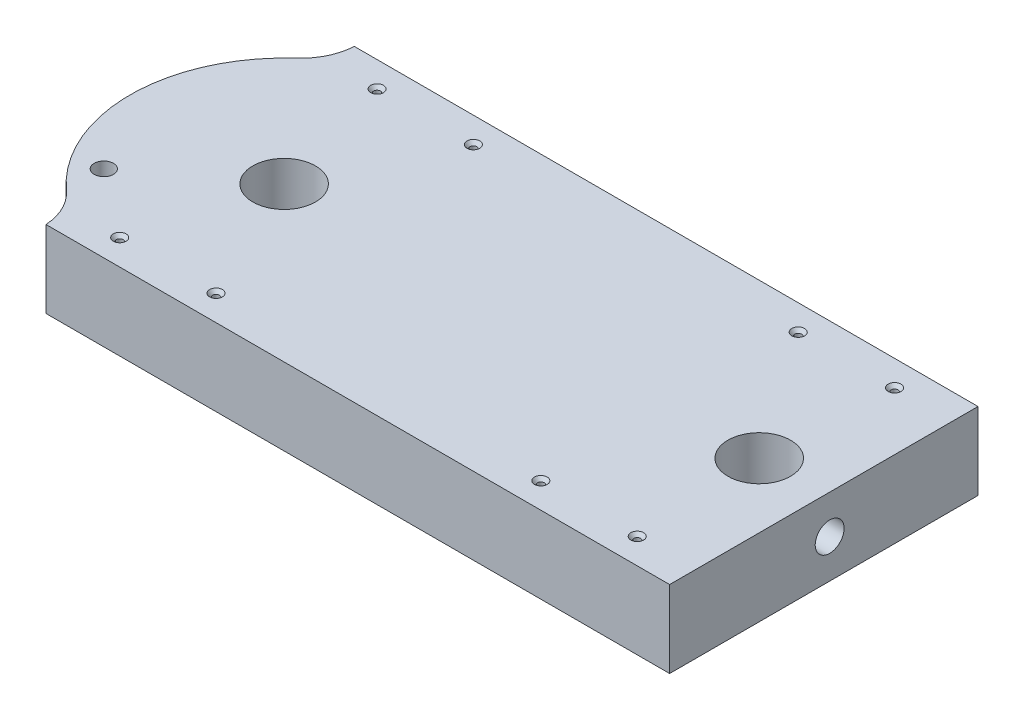
SolidWorks part; units mm, degrees
material "Pine"
ref_plane "Front Plane" through (0, 0, 0) normal (0, 0, 1) x (1, 0, 0)
ref_plane "Top Plane" through (0, 0, 0) normal (0, 1, 0) x (1, 0, 0)
ref_plane "Right Plane" through (0, 0, 0) normal (1, 0, 0) x (0, 0, -1)
other "Configuration Table"
sketch "Sketch1" plane through (0, 0, 0) normal (0, 1, 0) x (1, 0, 0)
  line L0 (0, -101.6) -> (-766.6236, -101.6) construction
  line L2 (0, 0) -> (0, -203.2)
  line L5 (-410.9201, 0) -> (-457.2, 0) construction
  line L7 (0, -203.2) -> (0, 0)
  line L9 (-457.2, -203.2) -> (-457.2, -137.1202) construction
  line L10 (-410.9201, -203.2) -> (-457.2, -203.2) construction
  line L11 (-457.2, -66.0798) -> (-457.2, 0) construction
  line L12 (-457.2, -137.1202) -> (-457.2, -66.0798) construction
  line L13 (-355.6, -101.6) -> (-355.6, -309.6499) construction
  line L14 (0, 0) -> (-410.9201, 0)
  line L15 (0, -203.2) -> (-410.9201, -203.2)
  arc A0 (-423.4899, -26.0122) -> (-423.4899, -177.1878) centre (-355.6, -101.6) ccw
  arc A1 (-423.4899, -26.0122) -> (-410.9201, 0) centre (-448.9486, 2.3333) ccw
  arc A2 (-410.9201, -203.2) -> (-423.4899, -177.1878) centre (-448.9486, -205.5333) ccw
  circle A3 centre (-355.6, -101.6) radius 101.6 construction
  circle A6 centre (-448.9486, 2.3333) radius 38.1 construction
  circle A7 centre (-448.9486, -205.5333) radius 38.1 construction
  dimension "D3" = 101.6
  dimension "D4" = 76.2
  dimension "D5" = 203.2
  dimension "D1" = 457.2
  dimension "D2" = 203.2
  dimension "D6" = 101.6
extrude "Boss-Extrude1" add sketch "Sketch1" along normal blind 50.8
sketch "Sketch2" plane through (0, 0, 203.2) normal (0, 0, 1) x (1, 0, 0)
  line L2 (-410.9201, 25.4) -> (-306.9829, 25.4) construction
  line L3 (-410.9201, 50.8) -> (-410.9201, 0) construction
  circle A0 centre (-370.5922, 25.4) radius 6.35
  dimension "D1" = 12.7
extrude "Cut-Extrude1" [suppressed] cut sketch "Sketch2" against normal blind 50.8
sketch "Sketch3" plane through (0, 0, 0) normal (1, 0, 0) x (0, 0, -1)
  line L0 (0, 25.4) -> (-248.5455, 25.4) construction
  line L1 (0, 50.8) -> (0, 0) construction
  line L2 (-101.6, 50.8) -> (-101.6, -50.7551) construction
  line L3 (0, 50.8) -> (-203.2, 50.8) construction
  circle A1 centre (-30.0783, 25.4) radius 6.35
  dimension "D1" = 12.7
extrude "Cut-Extrude2" [suppressed] cut sketch "Sketch3" against normal blind 50.8
sketch "Sketch4" plane through (0, 50.8, 0) normal (0, 1, 0) x (1, 0, 0)
  line L0 (0, -101.6) -> (-662.5845, -101.6) construction
  line L1 (0, 0) -> (0, -203.2) construction
sketch "Sketch5" plane through (0, 0, 203.2) normal (0, 0, 1) x (1, 0, 0)
  line L0 (0, 25.4) -> (-296.3789, 25.4) construction
  line L1 (0, 50.8) -> (0, 0) construction
  circle A0 centre (-66.3194, 25.4) radius 8.4944
  dimension "D1" = 66.3194
hole_wizard "5/8-11 Tapped Hole1" [suppressed] positions "Sketch6" profile "Sketch7" tap size "5/8-11" standard "ANSI Inch"
sketch "Sketch6" plane through (0, 0, 203.2) normal (0, 0, 1) x (1, 0, 0)
  point P0 (-66.3194, 12.7)
sketch "Sketch7" plane through (-66.3194, 12.7, 203.2) normal (1, 0, 0) x (0, -1, 0)
  line L0 (0, 0) -> (0, 22.225)
  line L1 (0, 22.225) -> (6.7462, 18.1715)
  line L2 (6.7462, 18.1715) -> (6.7462, 0)
  line L5 (6.7462, 0) -> (0, 0)
  line L10 (0, 22.225) -> (-6.7462, 18.1715) construction
  line L11 (0, -6.35) -> (0, 107.95) construction
  dimension "Tap Drill Dia." = 13.4925
  dimension "Tap Drill Depth" = 22.225
  dimension "Drill Angle" = 118
sketch "Sketch8" plane through (0, 0, 203.2) normal (0, 0, 1) x (1, 0, 0)
  line L0 (0, 50.8) -> (-662.5845, 50.8) construction
  line L1 (0, 0) -> (-132.6388, 0)
  line L2 (0, 0) -> (0, 50.8)
  line L3 (0, 50.8) -> (-132.6388, 50.8)
  line L4 (-132.6388, 0) -> (-132.6388, 50.8)
  dimension "D1" = 132.6388
extrude "Cut-Extrude3" [suppressed] cut sketch "Sketch8" against normal blind 38.1
hole_wizard "CSK for #8 Flat Head Machine Screw (100)1" positions "Sketch10" profile "Sketch12" countersink size "#8" standard "ANSI Inch" end condition through all
sketch "Sketch10" plane through (0, 50.8, 0) normal (0, 1, 0) x (1, 0, 0)
  line L0 (0, -203.2) -> (-410.9201, -203.2) construction
  point P0 (-379.1701, -186.3852)
  point P2 (-315.6701, -186.3852)
  dimension "D1" = 31.75
  dimension "D2" = 63.5
  dimension "D3" = 16.8148
sketch "Sketch12" plane through (-379.1701, 50.8, 186.3852) normal (1, 0, 0) x (0, 0, 1)
  line L0 (0, 0) -> (0, 50.8)
  line L1 (0, 50.8) -> (2.2479, 50.8)
  line L2 (2.2479, 50.8) -> (2.2479, 2.2645)
  line L3 (2.2479, 2.2645) -> (4.2164, 0)
  line L5 (4.2164, 0) -> (0, 0)
  line L6 (-2.2479, 2.2645) -> (-4.2164, 0) construction
  line L11 (0, -6.35) -> (0, 107.95) construction
  dimension "Thru Hole Dia." = 4.4958
  dimension "Thru Hole Depth" = 50.8
  dimension "Near C'Sink Dia." = 8.4328
  dimension "Near C'Sink Angle" = 82
ref_plane "Plane1" through (0, 0, 101.6) normal (0, 0, 1) x (1, 0, 0)
mirror "Mirror1" about plane through (0, 0, 101.6) normal (0, 0, 1) of "CSK for #8 Flat Head Machine Screw (100)1"
sketch "Sketch13" plane through (0, 50.8, 0) normal (0, 1, 0) x (1, 0, 0)
  line L0 (-208.661, 50.579) -> (-208.661, -369.1658) construction
  line L1 (0, 0) -> (0, -203.2) construction
  dimension "D1" = 410.9201
  dimension "D2" = 208.661
ref_plane "Plane2" through (-208.661, 0, 0) normal (1, 0, 0) x (0, 0, -1)
mirror "Mirror2" about plane through (-208.661, 0, 0) normal (1, 0, 0) of "Mirror1", "CSK for #8 Flat Head Machine Screw (100)1"
sketch "Sketch18" plane through (0, 50.8, 0) normal (0, 1, 0) x (1, 0, 0)
  line L0 (0, 0) -> (0, -203.2) construction
  line L2 (0, -203.2) -> (-410.9201, -203.2) construction
  circle A0 centre (-57.15, -146.05) radius 57.15 construction
  dimension "D1" = 114.3
sketch "Sketch14" plane through (0, 50.8, 0) normal (0, 1, 0) x (1, 0, 0)
  line L0 (0, -203.2) -> (-410.9201, -203.2) construction
  circle A0 centre (-423.6201, -152.4) radius 6.35
  dimension "D1" = 12.7
  dimension "D3" = 12.7
  dimension "D2" = 50.8
extrude "Cut-Extrude4" cut sketch "Sketch14" against normal through all
sketch "Sketch15" plane through (0, 50.8, 0) normal (0, 1, 0) x (1, 0, 0)
  line L0 (0, -101.6) -> (-662.5845, -101.6) construction
  circle A0 centre (-355.6, -101.6) radius 165.1 construction
  arc A1 (-423.4899, -26.0122) -> (-423.4899, -177.1878) centre (-355.6, -101.6) ccw construction
  circle A2 centre (-355.6, -101.6) radius 20.6375
  dimension "D1" = 330.2
  dimension "D2" = 41.275
extrude "Cut-Extrude5" cut sketch "Sketch15" against normal through all
sketch "Sketch16" plane through (0, 50.8, 0) normal (0, 1, 0) x (1, 0, 0)
  line L0 (0, -101.6) -> (-662.5845, -101.6) construction
  line L1 (0, 0) -> (0, -203.2) construction
  circle A0 centre (-42.545, -101.6) radius 20.6375
  circle A3 centre (-42.545, -101.6) radius 57.15 construction
  dimension "D1" = 41.275
  dimension "D2" = 42.545
extrude "Cut-Extrude6" cut sketch "Sketch16" against normal through all
sketch "Sketch17" plane through (0, 50.8, 0) normal (0, 1, 0) x (1, 0, 0)
  line L0 (-520.7, -101.6) -> (-520.7, -202.534) construction
  line L1 (0, -101.6) -> (0, -282.4079) construction
  circle A0 centre (-355.6, -101.6) radius 165.1 construction
  circle A1 centre (-42.545, -101.6) radius 82.55 construction
  dimension "D1" = 330.2
  dimension "D2" = 165.1
  dimension "D3" = 520.7
sketch "Sketch19" plane through (0, 50.8, 0) normal (0, 1, 0) x (1, 0, 0)
  line L0 (-355.6, -76.2) -> (-42.545, -76.2) construction
  line L1 (-355.6, -127) -> (-42.545, -127) construction
  line L2 (-355.6, -130.9624) -> (-42.545, -130.9624) construction
  line L3 (-355.6, -72.2376) -> (-42.545, -72.2376) construction
  arc A0 (-355.6, -76.2) -> (-355.6, -127) centre (-355.6, -101.6) ccw construction
  arc A1 (-42.545, -127) -> (-42.545, -76.2) centre (-42.545, -101.6) ccw construction
  circle A3 centre (-42.545, -101.6) radius 20.6375 construction
  arc A4 (-355.6, -72.2376) -> (-355.6, -130.9624) centre (-355.6, -101.6) ccw construction
  arc A5 (-42.545, -130.9624) -> (-42.545, -72.2376) centre (-42.545, -101.6) ccw construction
  dimension "D1" = 50.8
  dimension "D2" = 50.8
  dimension "D3" = 3.9624
hole_wizard "5/8 (0.75) Diameter Hole1" positions "Sketch20" profile "Sketch21" hole size "5/8" standard "ANSI Inch"
sketch "Sketch20" plane through (0, 0, 0) normal (1, 0, 0) x (0, 0, -1)
  line L7 (0, 25.4) -> (-54.4815, 25.4) construction
  line L8 (0, 50.8) -> (0, 0) construction
  point P0 (-97.7392, 25.4)
  point P25 (0, 0)
  dimension "D1" = 97.7392
sketch "Sketch21" plane through (0, 25.4, 97.7392) normal (0, 1, 0) x (0, 0, -1)
  line L0 (0, 0) -> (0, 38.6842)
  line L1 (0, 38.6842) -> (9.525, 32.961)
  line L2 (9.525, 32.961) -> (9.525, 0)
  line L5 (9.525, 0) -> (0, 0)
  line L10 (0, 38.6842) -> (-9.525, 32.961) construction
  line L11 (0, -6.35) -> (0, 107.95) construction
  dimension "Hole Dia." = 19.05
  dimension "Hole Depth" = 38.6842
  dimension "Drill Angle" = 118
